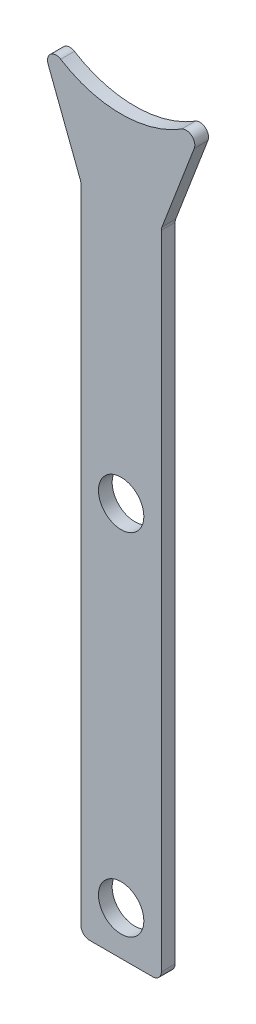
SolidWorks part; units mm, degrees
material "AISI 4130 Steel, annealed at 865C"
ref_plane "X-Y Datum" through (0, 0, 0) normal (0, 0, 1) x (1, 0, 0)
ref_plane "X-Z Datum" through (0, 0, 0) normal (0, 1, 0) x (1, 0, 0)
ref_plane "Y-Z Datum" through (0, 0, 0) normal (1, 0, 0) x (0, 0, -1)
sketch "Sketch1" plane through (0, 0, 0) normal (0, 0, 1) x (1, 0, 0)
  line L0 (-4.0676, 14.6842) -> (-4.0676, 15.9542) construction
  line L1 (1.1824, 14.6842) -> (1.1824, 15.9542) construction
  line L2 (-4.0676, 14.6842) -> (-4.0676, 13.4142) construction
  line L3 (1.1824, 14.6842) -> (1.1824, 13.4142) construction
  line L4 (-4.0676, -25.8288) -> (-4.0676, -24.5588) construction
  line L5 (1.1824, -25.8288) -> (1.1824, -24.5588) construction
  line L6 (-4.0676, -25.8288) -> (-4.0676, -27.0988) construction
  line L7 (1.1824, -25.8288) -> (1.1824, -27.0988) construction
  line L8 (-4.0676, -25.8288) -> (-6.0996, -25.8288) construction
  line L9 (-1.4426, -28.4538) -> (-1.4426, -30.9023) construction
  line L10 (1.1824, -25.8288) -> (3.2144, -25.8288) construction
  line L11 (-11.2713, 58.0661) -> (-6.0996, 44.5633)
  line L12 (3.2144, -30.9023) -> (-6.0996, -30.9023)
  line L13 (3.2144, -30.9023) -> (3.2144, 44.5633)
  line L15 (-6.0996, -30.9023) -> (-6.0996, 44.5633)
  line L16 (3.2144, 44.5633) -> (8.386, 58.0661)
  circle A0 centre (-1.4426, 14.6842) radius 2.625
  circle A1 centre (-1.4426, -25.8288) radius 2.625
  arc A3 (-11.2713, 58.0661) -> (8.386, 58.0661) centre (-1.4426, 66.8893) ccw
  dimension "D1" = 75.4656
  dimension "D2" = 5.0735
  dimension "D3" = 40.513
extrude "Boss-Extrude1" add sketch "Sketch1" along normal blind 1.5875
fillet "Fillet1" radius 1 6 edges at (-6.0996, -30.9023, 0.7937) (3.2144, -30.9023, 0.7937) (-6.0996, 44.5633, 0.7937) (3.2144, 44.5633, 0.7937) (-11.2713, 58.0661, 0.7937) (8.386, 58.0661, 0.7937)
